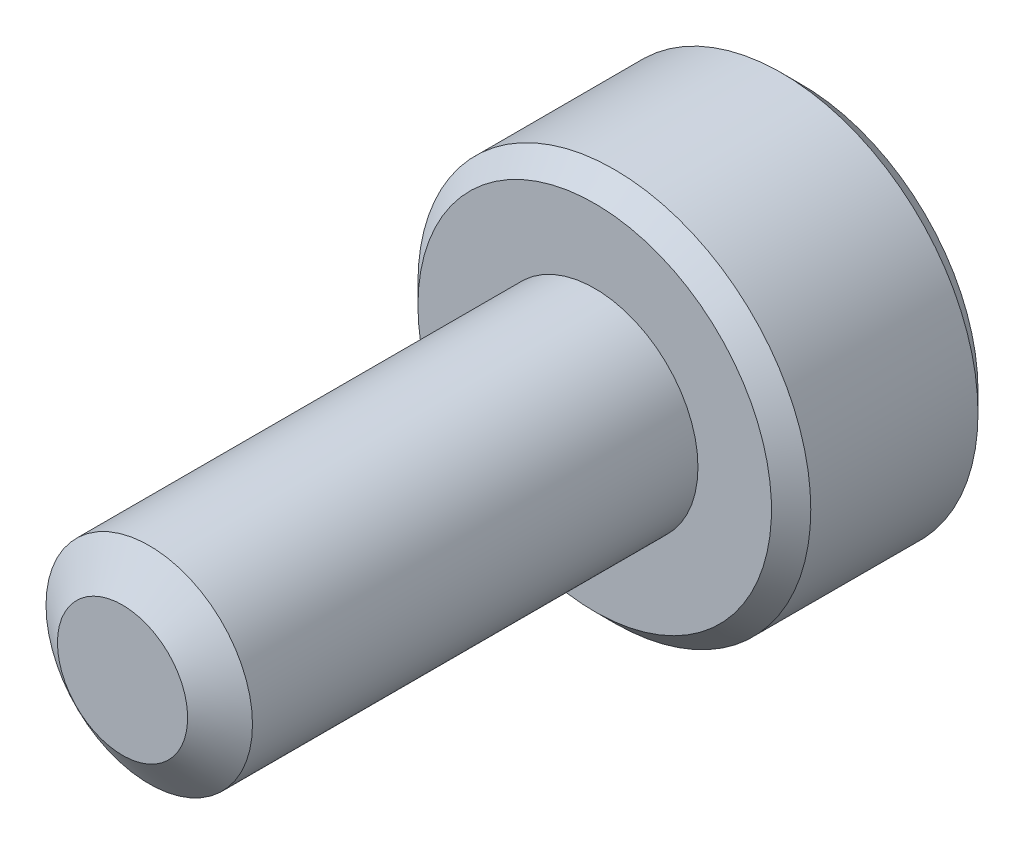
SolidWorks part; units mm, degrees
ref_plane "Front Plane" through (0, 0, 0) normal (0, 0, 1) x (1, 0, 0)
ref_plane "Top Plane" through (0, 0, 0) normal (0, 1, 0) x (1, 0, 0)
ref_plane "Right Plane" through (0, 0, 0) normal (1, 0, 0) x (0, 0, -1)
sketch "Sketch1" plane through (0, 0, 0) normal (0, 0, 1) x (1, 0, 0)
  circle A0 centre (0, 0) radius 2.0828
  dimension "D1" = 4.1656
extrude "Boss-Extrude1" add sketch "Sketch1" along normal blind 9.525
sketch "Sketch2" plane through (0, 0, 0) normal (1, 0, 0) x (0, 0, -1)
  line L0 (-9.525, 2.0828) -> (-9.525, 1.3132)
  line L1 (-9.525, 2.0828) -> (-9.525, -2.0828) construction
  line L2 (-9.525, 1.3132) -> (-8.9862, 2.0828)
  line L3 (0, 2.0828) -> (-9.525, 2.0828) construction
  line L4 (-8.9862, 2.0828) -> (-9.525, 2.0828)
  line L5 (0, 0) -> (-9.525, 0) construction
  dimension "D1" = 0.7696
  dimension "D2" = 55
revolve "Cut-Revolve1" cut sketch "Sketch2" angle 360 about L5
sketch "Sketch3" plane through (0, 0, 0) normal (0, 0, 1) x (1, 0, 0)
  circle A0 centre (0, 0) radius 3.9624
  dimension "D1" = 7.9248
extrude "Boss-Extrude2" add sketch "Sketch3" against normal blind 4.1656
sketch "Sketch4" plane through (0, 0, 0) normal (0, 0, 1) x (1, 0, 0)
  line L1 (0, -2.0622) -> (1.7859, -1.0311)
  line L2 (1.7859, -1.0311) -> (1.7859, 1.0311)
  line L3 (1.7859, 1.0311) -> (0, 2.0622)
  line L4 (0, 2.0622) -> (-1.7859, 1.0311)
  line L5 (-1.7859, 1.0311) -> (-1.7859, -1.0311)
  line L6 (-1.7859, -1.0311) -> (0, -2.0622)
  circle A0 centre (0, 0) radius 1.7859 construction
  dimension "D1" = 3.5719
extrude "Cut-Extrude1" cut sketch "Sketch4" along normal blind 2.6789 from surface at -4.1656 starting at face at (3.9624, 0, -4.1656)
sketch "Sketch5" plane through (0, 0, -4.1656) normal (0, 0, -1) x (-1, 0, 0)
  circle A0 centre (0, 0) radius 2.0622
extrude "Cut-Extrude2" cut sketch "Sketch5" against normal through all draft 45
chamfer "Chamfer1" distance 0.3962 angle 45 2 edges at (3.9624, 0, 0) (3.9624, 0, -4.1656)
sketch "Sketch6" [suppressed] plane through (0, 0, 0) normal (1, 0, 0) x (0, 0, -1)
  line L0 (0, 2.0828) -> (0, 4.5593)
  line L1 (0, 2.0828) -> (-3.5157, 2.0828)
  line L2 (0, 4.5593) -> (-0.2845, 4.5593)
  line L3 (-0.2845, 4.5593) -> (-2.8448, 2.3336)
  line L4 (0, 2.0828) -> (-8.9862, 2.0828) construction
  line L5 (0, 0) -> (-9.525, 0) construction
  line L6 (0, -2.0828) -> (0, 2.0828) construction
  line L7 (-9.525, 1.3132) -> (-9.525, -1.3132) construction
  arc A0 (-3.5157, 2.0828) -> (-2.8448, 2.3336) centre (-3.5157, 3.1055) ccw
  point P4 (0, 0)
  dimension "D1" = 4.5593
  dimension "D2" = 0.2845
  dimension "D3" = 2.8448
  dimension "D4" = 41
revolve "Revolve1" [suppressed] add sketch "Sketch6" angle 360 about L5
sketch "Sketch7" [suppressed] plane through (0, 0, 0) normal (0, 0, -1) x (-1, 0, 0)
  line L1 (-1.5875, -0.9165) -> (0, -1.8331)
  line L2 (0, -1.8331) -> (1.5875, -0.9165)
  line L3 (1.5875, -0.9165) -> (1.5875, 0.9165)
  line L4 (1.5875, 0.9165) -> (0, 1.8331)
  line L5 (0, 1.8331) -> (-1.5875, 0.9165)
  line L6 (-1.5875, 0.9165) -> (-1.5875, -0.9165)
  circle A0 centre (0, 0) radius 1.5875 construction
  dimension "D1" = 3.175
extrude "Cut-Extrude3" [suppressed] cut sketch "Sketch7" against normal blind 2.2581
sketch "Sketch8" [suppressed] plane through (0, 0, 0) normal (0, 0, -1) x (-1, 0, 0)
  circle A0 centre (0, 0) radius 1.8331
extrude "Cut-Extrude4" [suppressed] cut sketch "Sketch8" against normal through all draft 45
sketch "Sketch10" [suppressed] plane through (0, 0, 0) normal (1, 0, 0) x (0, 0, -1)
  line L0 (0, 0) -> (0, 3.9624)
  line L1 (0, 3.9624) -> (0.2721, 3.9624)
  line L2 (0, 0) -> (0.6385, 0)
  line L3 (0.6385, 0) -> (1.3259, 1.1906)
  line L4 (1.3259, 1.1906) -> (2.2098, 1.1906)
  line L5 (2.2098, 1.1906) -> (2.2098, 1.6669)
  line L6 (0, 0) -> (-4.1183, 0) construction
  arc A1 (0.2721, 3.9624) -> (2.2098, 1.6669) centre (-2.0935, 0) cw
  dimension "D1" = 0.2721
  dimension "D2" = 3.9624
  dimension "D3" = 0.6385
  dimension "D4" = 120
  dimension "D5" = 1.1906
  dimension "D6" = 1.6669
  dimension "D7" = 0.8839
revolve "Revolve2" [suppressed] add sketch "Sketch10" angle 360 about L6
sketch "Sketch11" [suppressed] plane through (0, 0, -2.2098) normal (0, 0, -1) x (-1, 0, 0)
  line L1 (-1.1906, -0.6874) -> (0, -1.3748)
  line L2 (0, -1.3748) -> (1.1906, -0.6874)
  line L3 (1.1906, -0.6874) -> (1.1906, 0.6874)
  line L4 (1.1906, 0.6874) -> (0, 1.3748)
  line L5 (0, 1.3748) -> (-1.1906, 0.6874)
  line L6 (-1.1906, 0.6874) -> (-1.1906, -0.6874)
  circle A0 centre (0, 0) radius 1.1906 construction
extrude "Cut-Extrude5" [suppressed] cut sketch "Sketch11" against normal up to vertex
sketch "Sketch12" [suppressed] plane through (0, 0, -2.2098) normal (0, 0, -1) x (-1, 0, 0)
  circle A0 centre (0, 0) radius 1.3748
extrude "Cut-Extrude6" [suppressed] cut sketch "Sketch12" against normal through all draft 45
sketch "Sketch13" [suppressed] plane through (0, 0, 0) normal (1, 0, 0) x (0, 0, -1)
  line L0 (0, 0) -> (0, 3.429)
  line L1 (0, -2.0828) -> (0, 2.0828) construction
  line L2 (0, 3.429) -> (1.6288, 3.429)
  line L3 (1.6288, 3.429) -> (1.9844, 3.0734)
  line L4 (1.9844, 3.0734) -> (1.9844, 0)
  line L5 (1.9844, 0) -> (0, 0)
  line L6 (0, 0) -> (-6.666, 0) construction
  dimension "D1" = 1.9844
  dimension "D2" = 3.429
  dimension "D3" = 3.0734
  dimension "D4" = 1.6288
revolve "Revolve3" [suppressed] add sketch "Sketch13" angle 360 about L6
sketch "Sketch14" [suppressed] plane through (0, 0, -1.9844) normal (0, 0, -1) x (-1, 0, 0)
  line L1 (0, -1.1457) -> (0.9922, -0.5728)
  line L2 (0.9922, -0.5728) -> (0.9922, 0.5728)
  line L3 (0.9922, 0.5728) -> (0, 1.1457)
  line L4 (0, 1.1457) -> (-0.9922, 0.5728)
  line L5 (-0.9922, 0.5728) -> (-0.9922, -0.5728)
  line L6 (-0.9922, -0.5728) -> (0, -1.1457)
  circle A0 centre (0, 0) radius 0.9922 construction
  dimension "D1" = 1.9844
extrude "Cut-Extrude7" [suppressed] cut sketch "Sketch14" against normal blind 1.524
sketch "Sketch15" [suppressed] plane through (0, 0, -1.9844) normal (0, 0, -1) x (-1, 0, 0)
  circle A0 centre (0, 0) radius 1.1457
extrude "Cut-Extrude8" [suppressed] cut sketch "Sketch15" against normal through all draft 45
equation "\"Length\"= .375"
equation "\"D1@Boss-Extrude1\"=\"Length\""
